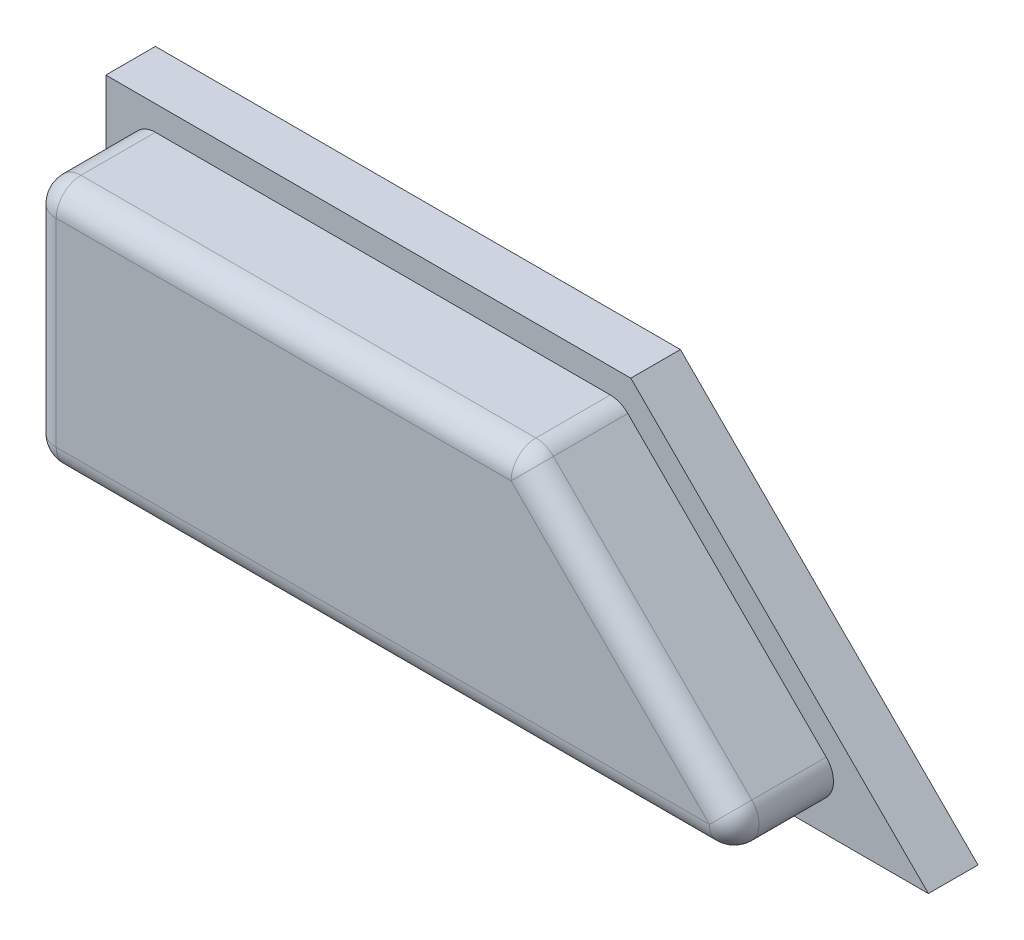
SolidWorks part; units mm, degrees
ref_plane "Front Plane" through (0, 0, 0) normal (0, 0, 1) x (1, 0, 0)
ref_plane "Top Plane" through (0, 0, 0) normal (0, 1, 0) x (1, 0, 0)
ref_plane "Right Plane" through (0, 0, 0) normal (1, 0, 0) x (0, 0, -1)
sketch "Sketch1" plane through (0, 0, 0) normal (0, 0, 1) x (1, 0, 0)
  line L0 (-0.4142, 7) -> (5.5858, 1)
  line L1 (5.5858, 1) -> (-0.4142, 1)
  line L6 (-11, 7) -> (-0.4142, 7)
  line L7 (-11, 7) -> (-11, 1)
  line L8 (-11, 1) -> (-0.4142, 1)
  dimension "D2" = 6
  dimension "D3" = 10.5858
  dimension "D4" = 6
  dimension "D10" = 10.5858
extrude "Boss-Extrude3" add sketch "Sketch1" along normal blind 1
sketch "Sketch4" plane through (0, 0, 1) normal (0, 0, 1) x (1, 0, 0)
  line L0 (-0.6213, 6.5) -> (4.3787, 1.5)
  line L1 (-10.5, 6.5) -> (-0.6213, 6.5)
  line L2 (-10.5, 6.5) -> (-10.5, 1.5)
  line L3 (-10.5, 1.5) -> (-0.6213, 1.5)
  line L5 (4.3787, 1.5) -> (-0.6213, 1.5)
  line L6 (-0.4142, 7) -> (-11, 7) construction
  line L7 (-11, 7) -> (-11, 1) construction
  line L8 (-11, 1) -> (5.5858, 1) construction
  line L9 (5.5858, 1) -> (-0.4142, 7) construction
  dimension "D1" = 0.5
  dimension "D2" = 0.5
  dimension "D3" = 0.5
  dimension "D4" = 0.5
  dimension "D5" = 0.5
extrude "Boss-Extrude4" add sketch "Sketch4" along normal blind 2
fillet "Fillet1" radius 0.5 8 edges at (1.8787, 4, 3) (-5.5607, 6.5, 3) (-10.5, 4, 3) (-3.0607, 1.5, 3) (4.3787, 1.5, 2) (-10.5, 1.5, 2) (-10.5, 6.5, 2) (-0.6213, 6.5, 2)
